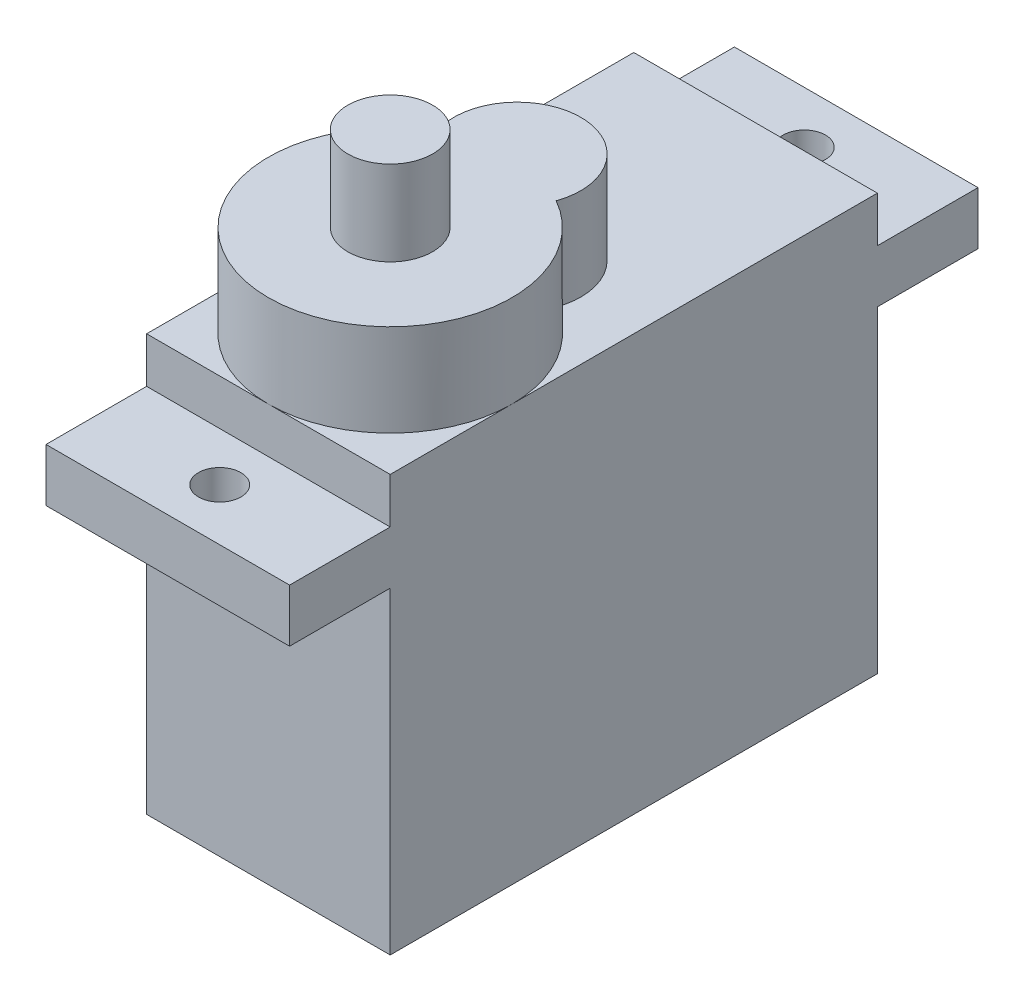
SolidWorks part; units mm, degrees
material "Servo"
ref_plane "前基準面" through (0, 0, 0) normal (0, 0, 1) x (1, 0, 0)
ref_plane "上基準面" through (0, 0, 0) normal (0, 1, 0) x (1, 0, 0)
ref_plane "右基準面" through (0, 0, 0) normal (1, 0, 0) x (0, 0, -1)
sketch "草圖1" plane through (0, 0, 0) normal (1, 0, 0) x (0, 0, -1)
  line L0 (11.5, 10) -> (16.25, 10)
  line L2 (-11.5, 7.5) -> (-11.5, -7.5)
  line L3 (-11.5, -7.5) -> (11.5, -7.5)
  line L4 (11.5, 7.5) -> (11.5, -7.5)
  line L5 (-11.5, 7.5) -> (11.5, -7.5) construction
  line L6 (-11.5, -7.5) -> (11.5, 7.5) construction
  line L7 (-16.25, 10) -> (-11.5, 10)
  line L8 (-16.25, 10) -> (-16.25, 7.5)
  line L9 (-16.25, 7.5) -> (-11.5, 7.5)
  line L10 (16.25, 10) -> (16.25, 7.5)
  line L11 (-16.25, 10) -> (16.25, 7.5) construction
  line L12 (-16.25, 7.5) -> (16.25, 10) construction
  line L13 (-11.5, 12.15) -> (11.5, 12.15)
  line L14 (-11.5, 12.15) -> (-11.5, 10)
  line L16 (11.5, 12.15) -> (11.5, 10)
  line L17 (-11.5, 12.15) -> (11.5, 10) construction
  line L18 (-11.5, 10) -> (11.5, 12.15) construction
  line L19 (11.5, 7.5) -> (16.25, 7.5)
  line L20 (0, 11.075) -> (0, 0) construction
  point P0 (0, 0)
  point P6 (0, 8.75)
  point P11 (0, 11.075)
  dimension "D1" = 23
  dimension "D2" = 15
  dimension "D3" = 19.65
  dimension "D4" = 2.5
  dimension "D5" = 32.5
extrude "填料-伸長1" add sketch "草圖1" along normal blind 11.5
sketch "草圖2" plane through (0, 12.15, 0) normal (0, 1, 0) x (1, 0, 0)
  line L1 (11.5, -11.5) -> (0, -11.5) construction
  line L3 (0, 11.5) -> (0, -11.5) construction
  line L4 (11.5, 11.5) -> (11.5, -11.5) construction
  line L5 (5.75, -11.5) -> (5.75, 11.5) construction
  line L6 (11.5, 11.5) -> (0, 11.5) construction
  arc A0 (2.9197, -0.7448) -> (8.5803, -0.7448) centre (5.75, -5.75) ccw
  arc A1 (8.5803, -0.7448) -> (2.9197, -0.7448) centre (5.75, 0.25) ccw
  dimension "D1" = 6
  dimension "D2" = 6
extrude "填料-伸長2" add sketch "草圖2" along normal blind 4.35
sketch "草圖3" plane through (0, 16.5, 0) normal (0, 1, 0) x (1, 0, 0)
  circle A0 centre (5.75, -5.75) radius 2
  dimension "D1" = 4
extrude "填料-伸長3" add sketch "草圖3" along normal blind 4
sketch "草圖4" plane through (0, 10, 0) normal (0, 1, 0) x (1, 0, 0)
  line L0 (5.75, -16.25) -> (5.75, 16.25) construction
  line L1 (11.5, -16.25) -> (0, -16.25) construction
  line L2 (11.5, 16.25) -> (0, 16.25) construction
  line L3 (5.75, -13.8) -> (5.75, 13.8) construction
  circle A0 centre (5.75, -13.8) radius 1
  circle A1 centre (5.75, 13.8) radius 1
  point P10 (5.75, 0)
  dimension "D3" = 2
  dimension "D1" = 27.6
extrude "除料-伸長1" cut sketch "草圖4" against normal through all
